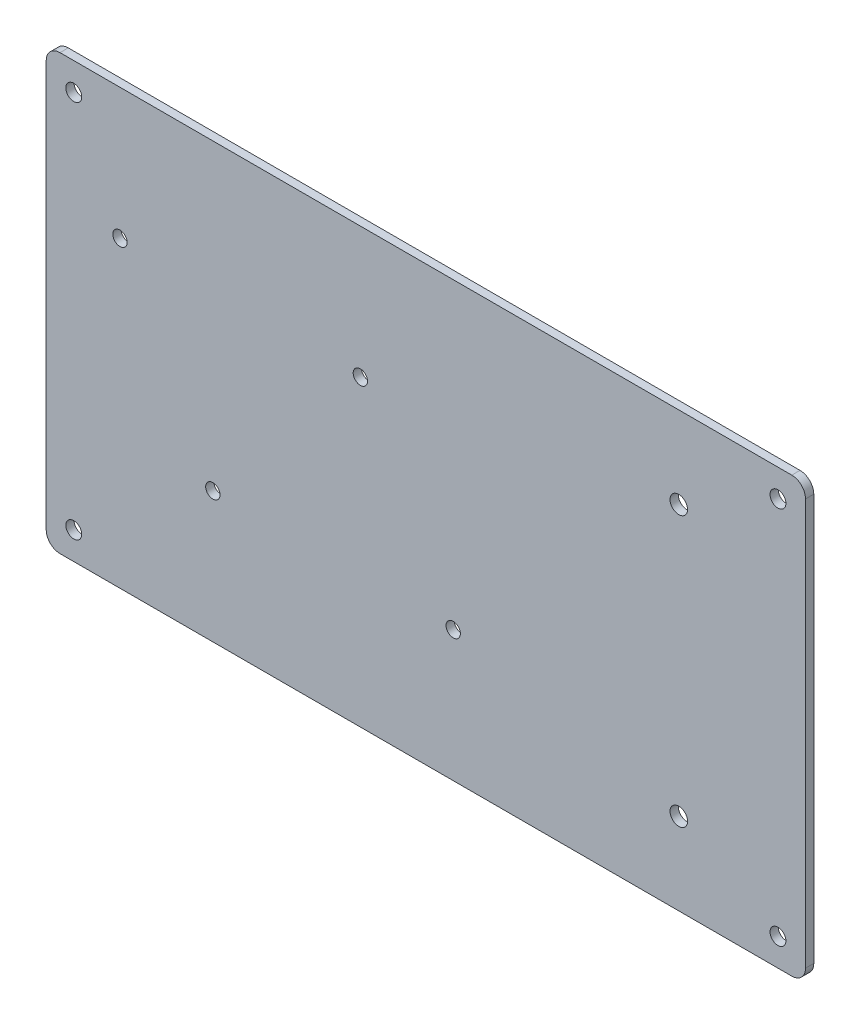
SolidWorks part; units mm, degrees
ref_plane "Front Plane" through (0, 0, 0) normal (0, 0, 1) x (1, 0, 0)
ref_plane "Top Plane" through (0, 0, 0) normal (0, 1, 0) x (1, 0, 0)
ref_plane "Right Plane" through (0, 0, 0) normal (1, 0, 0) x (0, 0, -1)
sketch "Sketch1" plane through (0, 0, 0) normal (0, 0, 1) x (1, 0, 0)
  line L1 (-87.5, -50) -> (87.5, -50)
  line L2 (-87.5, -50) -> (-87.5, 50)
  line L3 (-87.5, 50) -> (87.5, 50)
  line L4 (87.5, -50) -> (87.5, 50)
  line L5 (-87.5, -50) -> (87.5, 50) construction
  line L6 (-87.5, 50) -> (87.5, -50) construction
  point P0 (0, 0)
  dimension "D1" = 100
  dimension "D2" = 175
extrude "Boss-Extrude1" add sketch "Sketch1" along normal blind 1.9
sketch "Sketch2" plane through (0, 0, 0) normal (0, 0, -1) x (-1, 0, 0)
  line L2 (-87.5, 50) -> (87.5, 50) construction
  line L3 (-87.5, -50) -> (-87.5, 50) construction
  line L5 (55, 0) -> (-55, 0) construction
  line L6 (0, 55) -> (0, -55) construction
  circle A0 centre (-81.15, 43.65) radius 1.8288
  circle A1 centre (-81.15, -43.65) radius 1.8288
  circle A2 centre (81.15, 43.65) radius 1.8288
  circle A3 centre (81.15, -43.65) radius 1.8288
  point P2 (0, 0)
  point P3 (0, 0)
  point P6 (0, 0)
  dimension "D1" = 3.6576
  dimension "D2" = 6.35
  dimension "D3" = 6.35
extrude "Cut-Extrude1" cut sketch "Sketch2" against normal up to next and the other way through all
fillet "Fillet1" radius 3.175 4 edges at (87.5, -50, 0.95) (-87.5, -50, 0.95) (-87.5, 50, 0.95) (87.5, 50, 0.95)
sketch "Sketch3" plane through (0, 0, 1.9) normal (0, 0, 1) x (1, 0, 0)
  circle A0 centre (-49.1, -19.85) radius 1.65
  arc A1 (-49.1, -21.5) -> (-49.1, -18.2) centre (-49.1, -19.85) ccw construction
  circle A2 centre (-70.5, 19.85) radius 1.65
  arc A3 (-70.5, 21.5) -> (-70.5, 18.2) centre (-70.5, 19.85) ccw construction
  circle A4 centre (6.3, -19.85) radius 1.65
  arc A5 (6.3, -18.2) -> (6.3, -21.5) centre (6.3, -19.85) ccw construction
  circle A6 centre (-15.1, 19.85) radius 1.65
  arc A7 (-15.1, 21.5) -> (-15.1, 18.2) centre (-15.1, 19.85) ccw construction
  circle A8 centre (58.29, -31.115) radius 2.0193
  circle A9 centre (58.29, 31.115) radius 2.0193
  ellipse E0 centre (58.29, 31.115) end of major axis (60.3093, 31.115) minor radius 2.0193 construction
  ellipse E1 centre (58.29, -31.115) end of major axis (60.3093, -31.115) minor radius 2.0193 construction
  point P33 (52.14, -31.115)
  point P36 (52.14, 30.906)
extrude "Cut-Extrude2" cut sketch "Sketch3" against normal up to next
